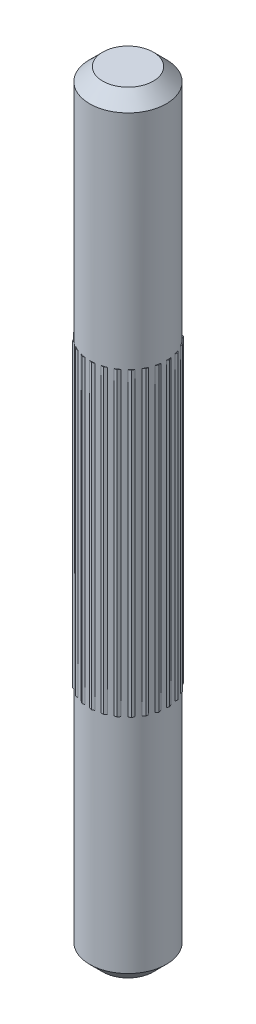
SolidWorks part; units mm, degrees
ref_plane "Front Plane" through (0, 0, 0) normal (0, 0, 1) x (1, 0, 0)
ref_plane "Top Plane" through (0, 0, 0) normal (0, 1, 0) x (1, 0, 0)
ref_plane "Right Plane" through (0, 0, 0) normal (1, 0, 0) x (0, 0, -1)
sketch "Sketch1" plane through (0, 0, 0) normal (0, 1, 0) x (1, 0, 0)
  circle A0 centre (0, 0) radius 1.465
  dimension "D1" = 2.93
extrude "Extrude1" add sketch "Sketch1" along normal mid plane 29.5
chamfer "Chamfer1" distance 0.5 angle 45 2 edges at (0, 14.75, 1.465) (0, -14.75, 1.465)
sketch "Sketch2" plane through (0, 0, 0) normal (0, 1, 0) x (1, 0, 0)
  line L0 (0, 0) -> (0, 1.571) construction
  line L1 (0, 0) -> (0.4172, 1.5569) construction
  line L2 (0.1912, 1.4525) -> (0.2926, 1.4712)
  line L3 (0.2926, 1.4712) -> (0.3792, 1.4151)
  line L4 (0.5606, 1.3535) -> (0.6634, 1.3453)
  line L5 (0.6634, 1.3453) -> (0.7325, 1.2687)
  line L6 (0.8918, 1.1623) -> (0.989, 1.1278)
  line L7 (0.989, 1.1278) -> (1.0359, 1.0359)
  line L8 (1.1623, 0.8918) -> (1.2472, 0.8334)
  line L9 (1.2472, 0.8334) -> (1.2687, 0.7325)
  line L10 (1.3535, 0.5606) -> (1.4204, 0.4822)
  line L11 (1.4204, 0.4822) -> (1.4151, 0.3792)
  line L12 (1.4525, 0.1912) -> (1.4968, 0.0981)
  line L13 (1.4968, 0.0981) -> (1.465, 0)
  line L14 (1.4525, -0.1912) -> (1.4712, -0.2926)
  line L15 (1.4712, -0.2926) -> (1.4151, -0.3792)
  line L16 (1.3535, -0.5606) -> (1.3453, -0.6634)
  line L17 (1.3453, -0.6634) -> (1.2687, -0.7325)
  line L18 (1.1623, -0.8918) -> (1.1278, -0.989)
  line L19 (1.1278, -0.989) -> (1.0359, -1.0359)
  line L20 (0.8918, -1.1623) -> (0.8334, -1.2472)
  line L21 (0.8334, -1.2472) -> (0.7325, -1.2687)
  line L22 (0.5606, -1.3535) -> (0.4822, -1.4204)
  line L23 (0.4822, -1.4204) -> (0.3792, -1.4151)
  line L24 (0.1912, -1.4525) -> (0.0981, -1.4968)
  line L25 (0.0981, -1.4968) -> (0, -1.465)
  line L26 (-0.1912, -1.4525) -> (-0.2926, -1.4712)
  line L27 (-0.2926, -1.4712) -> (-0.3792, -1.4151)
  line L28 (-0.5606, -1.3535) -> (-0.6634, -1.3453)
  line L29 (-0.6634, -1.3453) -> (-0.7325, -1.2687)
  line L30 (-0.8918, -1.1623) -> (-0.989, -1.1278)
  line L31 (-0.989, -1.1278) -> (-1.0359, -1.0359)
  line L32 (-1.1623, -0.8918) -> (-1.2472, -0.8334)
  line L33 (-1.2472, -0.8334) -> (-1.2687, -0.7325)
  line L34 (-1.3535, -0.5606) -> (-1.4204, -0.4822)
  line L35 (-1.4204, -0.4822) -> (-1.4151, -0.3792)
  line L36 (-1.4525, -0.1912) -> (-1.4968, -0.0981)
  line L37 (-1.4968, -0.0981) -> (-1.465, 0)
  line L38 (-1.4525, 0.1912) -> (-1.4712, 0.2926)
  line L39 (-1.4712, 0.2926) -> (-1.4151, 0.3792)
  line L40 (-1.3535, 0.5606) -> (-1.3453, 0.6634)
  line L41 (-1.3453, 0.6634) -> (-1.2687, 0.7325)
  line L42 (-1.1623, 0.8918) -> (-1.1278, 0.989)
  line L43 (-1.1278, 0.989) -> (-1.0359, 1.0359)
  line L44 (-0.8918, 1.1623) -> (-0.8334, 1.2472)
  line L45 (-0.8334, 1.2472) -> (-0.7325, 1.2687)
  line L46 (-0.5606, 1.3535) -> (-0.4822, 1.4204)
  line L47 (-0.4822, 1.4204) -> (-0.3792, 1.4151)
  line L48 (-0.1912, 1.4525) -> (-0.0981, 1.4968)
  line L49 (-0.0981, 1.4968) -> (0, 1.465)
  arc A0 (0, 1.465) -> (0.1912, 1.4525) centre (0, 0) cw
  circle A1 centre (0, 0) radius 1.465 construction
  arc A2 (0.3792, 1.4151) -> (0.5606, 1.3535) centre (0, 0) cw
  arc A3 (0.7325, 1.2687) -> (0.8918, 1.1623) centre (0, 0) cw
  arc A4 (1.0359, 1.0359) -> (1.1623, 0.8918) centre (0, 0) cw
  arc A5 (1.2687, 0.7325) -> (1.3535, 0.5606) centre (0, 0) cw
  arc A6 (1.4151, 0.3792) -> (1.4525, 0.1912) centre (0, 0) cw
  arc A7 (1.465, 0) -> (1.4525, -0.1912) centre (0, 0) cw
  arc A8 (1.4151, -0.3792) -> (1.3535, -0.5606) centre (0, 0) cw
  arc A9 (1.2687, -0.7325) -> (1.1623, -0.8918) centre (0, 0) cw
  arc A10 (1.0359, -1.0359) -> (0.8918, -1.1623) centre (0, 0) cw
  arc A11 (0.7325, -1.2687) -> (0.5606, -1.3535) centre (0, 0) cw
  arc A12 (0.3792, -1.4151) -> (0.1912, -1.4525) centre (0, 0) cw
  arc A13 (0, -1.465) -> (-0.1912, -1.4525) centre (0, 0) cw
  arc A14 (-0.3792, -1.4151) -> (-0.5606, -1.3535) centre (0, 0) cw
  arc A15 (-0.7325, -1.2687) -> (-0.8918, -1.1623) centre (0, 0) cw
  arc A16 (-1.0359, -1.0359) -> (-1.1623, -0.8918) centre (0, 0) cw
  arc A17 (-1.2687, -0.7325) -> (-1.3535, -0.5606) centre (0, 0) cw
  arc A18 (-1.4151, -0.3792) -> (-1.4525, -0.1912) centre (0, 0) cw
  arc A19 (-1.465, 0) -> (-1.4525, 0.1912) centre (0, 0) cw
  arc A20 (-1.4151, 0.3792) -> (-1.3535, 0.5606) centre (0, 0) cw
  arc A21 (-1.2687, 0.7325) -> (-1.1623, 0.8918) centre (0, 0) cw
  arc A22 (-1.0359, 1.0359) -> (-0.8918, 1.1623) centre (0, 0) cw
  arc A23 (-0.7325, 1.2687) -> (-0.5606, 1.3535) centre (0, 0) cw
  arc A24 (-0.3792, 1.4151) -> (-0.1912, 1.4525) centre (0, 0) cw
  dimension "D1" = 15
  dimension "D2" = 1.5
  dimension "D3" = 7.5
extrude "Extrude2" add sketch "Sketch2" along normal mid plane 11.5
